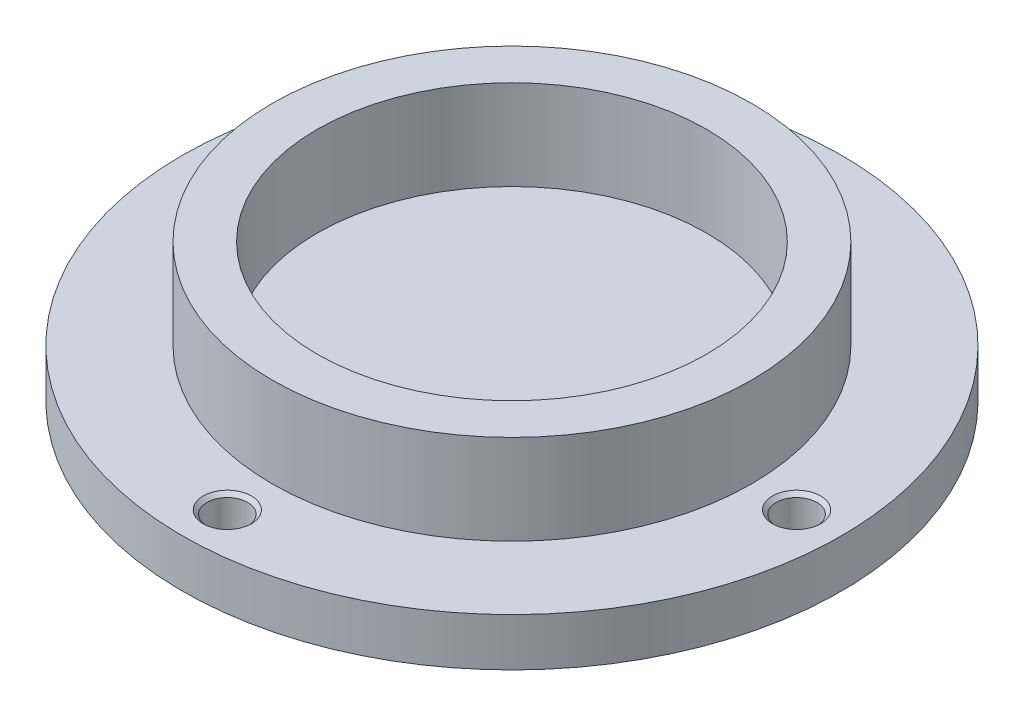
SolidWorks part; units mm, degrees
ref_plane "前视基准面" through (0, 0, 0) normal (0, 0, 1) x (1, 0, 0)
ref_plane "上视基准面" through (0, 0, 0) normal (0, 1, 0) x (1, 0, 0)
ref_plane "右视基准面" through (0, 0, 0) normal (1, 0, 0) x (0, 0, -1)
other "Configuration Table"
sketch "草图1" plane through (0, 0, 0) normal (0, 0, 1) x (1, 0, 0)
  line L0 (0, 34.8163) -> (0, -25.9388) construction
  line L1 (0, 0) -> (55, 0)
  line L2 (55, 0) -> (55, 8)
  line L3 (55, 8) -> (40, 8)
  line L4 (40, 8) -> (40, 23)
  line L5 (40, 23) -> (32.5, 23)
  line L6 (32.5, 23) -> (32.5, 8)
  line L7 (32.5, 8) -> (0, 8)
  line L8 (0, 8) -> (0, 0)
  dimension "D1" = 32.5
  dimension "D2" = 7.5
  dimension "D3" = 8
  dimension "D4" = 15
  dimension "D5" = 55
revolve "旋转1" add sketch "草图1" angle 360 about L8
sketch "草图2" plane through (0, 0, 0) normal (0, 1, 0) x (1, 0, 0)
  circle A0 centre (0, 0) radius 47.5
  circle A1 centre (47.5, 0) radius 4.5
  circle A2 centre (0, -47.5) radius 4.5
  circle A3 centre (-47.5, 0) radius 4.5
  circle A4 centre (0, 47.5) radius 4.5
  point P14 (0, 0)
  dimension "D1" = 4
  dimension "D2" = 95
hole_wizard "M8 螺纹孔1" positions "草图7" profile "草图8" tap size "M8" standard "GB" end condition through all
sketch "草图7" plane through (0, 8, 0) normal (0, 1, 0) x (1, 0, 0)
  point P0 (-47.5, 0)
  point P3 (47.5, 0)
  point P6 (0, -47.5)
  point P9 (0, 47.5)
sketch "草图8" plane through (-47.5, 8, 0) normal (1, 0, 0) x (0, 0, 1)
  line L0 (0, 0) -> (0, 8)
  line L1 (0, 8) -> (3.4, 8)
  line L2 (3.4, 8) -> (3.4, 0.625)
  line L3 (3.4, 0.625) -> (4.025, 0)
  line L5 (4.025, 0) -> (0, 0)
  line L6 (-3.4, 0.625) -> (-4.025, 0) construction
  line L11 (0, -6.35) -> (0, 107.95) construction
  dimension "通孔螺纹孔钻头直径" = 6.8
  dimension "通孔螺纹孔钻头深度" = 8
  dimension "近端锥形沉头孔直径" = 8.05
  dimension "近端锥形沉头孔角度" = 90
cosmetic thread "孔螺蚊线1" parameters "D2"=8
cosmetic thread "孔螺蚊线2" parameters "D2"=8
cosmetic thread "孔螺蚊线3" parameters "D2"=8
cosmetic thread "孔螺蚊线4" parameters "D2"=8
sketch "草图3" plane through (0, 0, 0) normal (0, 1, 0) x (1, 0, 0)
  circle A0 centre (0, 0) radius 21
extrude "切除-拉伸3" [suppressed] cut sketch "草图3" along normal blind 21
sketch "草图4" plane through (0, 0, 0) normal (1, 0, 0) x (0, 0, -1)
  line L0 (0, 0) -> (0, 4)
  line L1 (0, 4) -> (10.5, 4)
  line L2 (25.5, 4) -> (25.5, 1)
  line L3 (25.5, 1) -> (21, 1)
  line L5 (21, 7) -> (25.5, 7)
  line L6 (25.5, 7) -> (25.5, 4)
  line L7 (0, 0) -> (0, 13.0193) construction
  line L8 (21, 7) -> (10.5, 7)
  line L9 (0, 7) -> (0, 1)
  line L10 (10.5, 7) -> (10.5, 1)
  line L11 (10.5, 1) -> (21, 1)
revolve "切除-旋转2" [suppressed] cut sketch "草图4" angle 360 about L7
